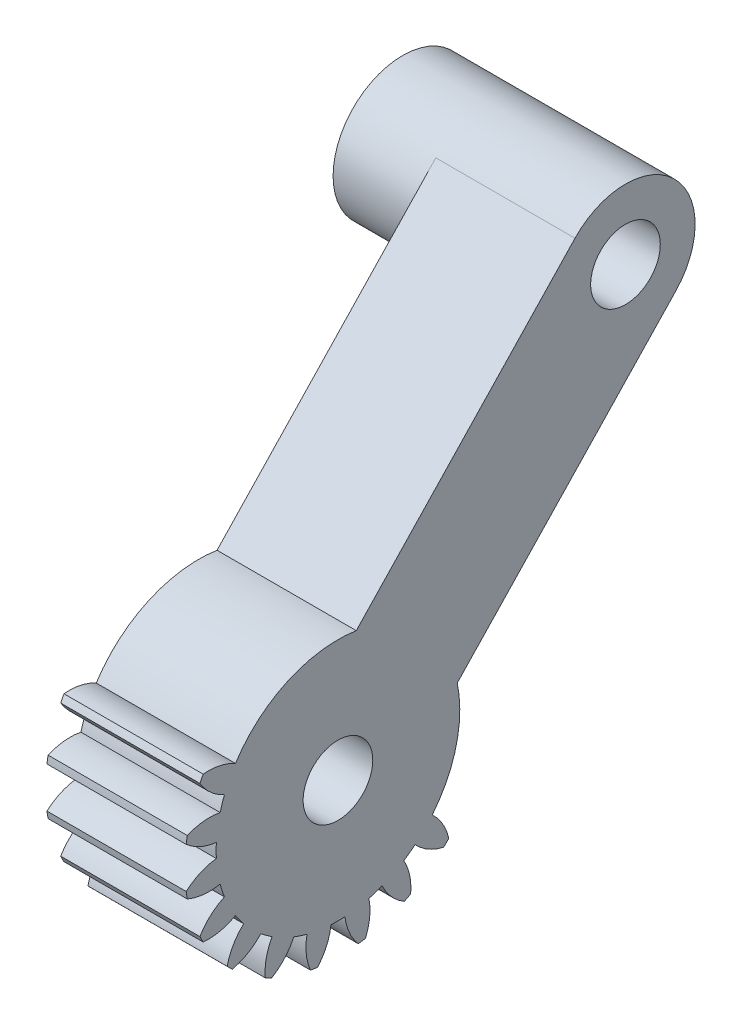
SolidWorks part; units mm, degrees
ref_plane "Front Plane" through (0, 0, 0) normal (0, 0, 1) x (1, 0, 0)
ref_plane "Top Plane" through (0, 0, 0) normal (0, 1, 0) x (1, 0, 0)
ref_plane "Right Plane" through (0, 0, 0) normal (1, 0, 0) x (0, 0, -1)
ref_plane "Plane1" through (4.0439, 0, 0) normal (1, 0, 0) x (0, 0, -1)
sketch "Sketch1" plane through (4.0439, 0, 0) normal (1, 0, 0) x (0, 0, -1)
  circle A0 centre (0.8725, -1.1221) radius 2.5
  arc A1 (-10.0295, 0.3429) -> (-7.8622, -0.6222) centre (-7.392, 3.3501) ccw
  arc A2 (-7.8622, -0.6222) -> (-7.8622, -1.622) centre (0.8725, -1.1221) ccw
  arc A3 (-7.8622, -1.622) -> (-10.0295, -2.587) centre (-7.392, -5.5943) ccw
  arc A4 (-10.0295, -2.587) -> (-9.9487, -3.0977) centre (0.8725, -1.1221) ccw
  arc A5 (-9.9487, -3.0977) -> (-7.5892, -3.3458) centre (-8.3695, 0.5774) ccw
  arc A6 (-7.5892, -3.3458) -> (-7.2802, -4.2967) centre (0.8725, -1.1221) ccw
  arc A7 (-7.2802, -4.2967) -> (-9.0433, -5.8842) centre (-5.6055, -7.9292) ccw
  arc A8 (-9.0433, -5.8842) -> (-8.8085, -6.3449) centre (0.8725, -1.1221) ccw
  arc A9 (-8.8085, -6.3449) -> (-6.4879, -5.8518) centre (-8.4423, -2.3617) ccw
  arc A10 (-6.4879, -5.8518) -> (-5.9002, -6.6607) centre (0.8725, -1.1221) ccw
  arc A11 (-5.9002, -6.6607) -> (-7.0864, -8.7153) centre (-3.185, -9.5979) ccw
  arc A12 (-7.0864, -8.7153) -> (-6.7207, -9.0809) centre (0.8725, -1.1221) ccw
  arc A13 (-6.7207, -9.0809) -> (-4.6661, -7.8948) centre (-7.6033, -5.1795) ccw
  arc A14 (-4.6661, -7.8948) -> (-3.8572, -8.4825) centre (0.8725, -1.1221) ccw
  arc A15 (-3.8572, -8.4825) -> (-4.3504, -10.8031) centre (-0.3672, -10.4369) ccw
  arc A16 (-4.3504, -10.8031) -> (-3.8897, -11.0378) centre (0.8725, -1.1221) ccw
  arc A17 (-3.8897, -11.0378) -> (-2.3022, -9.2748) centre (-5.9347, -7.6001) ccw
  arc A18 (-2.3022, -9.2748) -> (-1.3512, -9.5838) centre (0.8725, -1.1221) ccw
  arc A19 (-1.3512, -9.5838) -> (-1.1032, -11.9432) centre (2.5719, -10.3641) ccw
  arc A20 (-1.1032, -11.9432) -> (-0.5925, -12.0241) centre (0.8725, -1.1221) ccw
  arc A21 (-0.5925, -12.0241) -> (0.3725, -9.8568) centre (-3.5997, -9.3866) ccw
  arc A22 (0.3725, -9.8568) -> (1.3724, -9.8568) centre (0.8725, -1.1221) ccw
  arc A23 (1.3724, -9.8568) -> (2.3374, -12.0241) centre (5.3447, -9.3866) ccw
  arc A24 (2.3374, -12.0241) -> (2.8481, -11.9432) centre (0.8725, -1.1221) ccw
  arc A25 (2.8481, -11.9432) -> (3.0962, -9.5838) centre (-0.827, -10.3641) ccw
  arc A26 (3.0962, -9.5838) -> (4.0471, -9.2748) centre (0.8725, -1.1221) ccw
  arc A27 (4.0471, -9.2748) -> (5.6346, -11.0378) centre (7.6796, -7.6001) ccw
  arc A28 (5.6346, -11.0378) -> (6.0953, -10.8031) centre (0.8725, -1.1221) ccw
  arc A29 (6.0953, -10.8031) -> (5.6022, -8.4825) centre (2.1121, -10.4369) ccw
  arc A30 (5.6022, -8.4825) -> (6.411, -7.8948) centre (0.8725, -1.1221) ccw
  arc A31 (6.411, -7.8948) -> (8.4657, -9.0809) centre (9.3483, -5.1795) ccw
  arc A32 (8.4657, -9.0809) -> (8.8313, -8.7153) centre (0.8725, -1.1221) ccw
  arc A33 (8.8313, -8.7153) -> (7.6451, -6.6607) centre (4.9299, -9.5979) ccw
  arc A34 (7.6451, -6.6607) -> (8.2328, -5.8518) centre (0.8725, -1.1221) ccw
  arc A35 (8.2328, -5.8518) -> (10.5535, -6.3449) centre (10.1873, -2.3617) ccw
  arc A36 (10.5535, -6.3449) -> (10.7882, -5.8842) centre (0.8725, -1.1221) ccw
  arc A37 (10.7882, -5.8842) -> (9.0252, -4.2967) centre (7.3505, -7.9292) ccw
  arc A38 (9.0252, -4.2967) -> (9.3342, -3.3458) centre (0.8725, -1.1221) ccw
  arc A39 (9.3342, -3.3458) -> (11.6936, -3.0977) centre (10.1144, 0.5774) ccw
  arc A40 (11.6936, -3.0977) -> (11.7745, -2.587) centre (0.8725, -1.1221) ccw
  arc A41 (11.7745, -2.587) -> (9.6072, -1.622) centre (9.137, -5.5943) ccw
  arc A42 (9.6072, -1.622) -> (9.6072, -0.6222) centre (0.8725, -1.1221) ccw
  arc A43 (9.6072, -0.6222) -> (11.7745, 0.3429) centre (9.137, 3.3501) ccw
  arc A44 (11.7745, 0.3429) -> (11.6936, 0.8536) centre (0.8725, -1.1221) ccw
  arc A45 (11.6936, 0.8536) -> (9.3342, 1.1016) centre (10.1144, -2.8215) ccw
  arc A46 (9.3342, 1.1016) -> (9.0252, 2.0526) centre (0.8725, -1.1221) ccw
  arc A47 (9.0252, 2.0526) -> (10.7882, 3.6401) centre (7.3505, 5.6851) ccw
  arc A48 (10.7882, 3.6401) -> (10.5535, 4.1008) centre (0.8725, -1.1221) ccw
  arc A49 (10.5535, 4.1008) -> (8.2328, 3.6076) centre (10.1873, 0.1176) ccw
  arc A50 (8.2328, 3.6076) -> (7.6451, 4.4165) centre (0.8725, -1.1221) ccw
  arc A51 (7.6451, 4.4165) -> (8.8313, 6.4711) centre (4.9299, 7.3537) ccw
  arc A52 (8.8313, 6.4711) -> (8.4657, 6.8368) centre (0.8725, -1.1221) ccw
  arc A53 (8.4657, 6.8368) -> (6.411, 5.6506) centre (9.3483, 2.9353) ccw
  arc A54 (6.411, 5.6506) -> (5.6022, 6.2383) centre (0.8725, -1.1221) ccw
  arc A55 (5.6022, 6.2383) -> (6.0953, 8.5589) centre (2.1121, 8.1927) ccw
  arc A56 (6.0953, 8.5589) -> (5.6346, 8.7937) centre (0.8725, -1.1221) ccw
  arc A57 (5.6346, 8.7937) -> (4.0471, 7.0306) centre (7.6796, 5.3559) ccw
  arc A58 (4.0471, 7.0306) -> (3.0962, 7.3396) centre (0.8725, -1.1221) ccw
  arc A59 (3.0962, 7.3396) -> (2.8481, 9.6991) centre (-0.827, 8.1199) ccw
  arc A60 (2.8481, 9.6991) -> (2.3374, 9.7799) centre (0.8725, -1.1221) ccw
  arc A61 (2.3374, 9.7799) -> (1.3724, 7.6126) centre (5.3447, 7.1424) ccw
  arc A62 (1.3724, 7.6126) -> (0.3725, 7.6126) centre (0.8725, -1.1221) ccw
  arc A63 (0.3725, 7.6126) -> (-0.5925, 9.7799) centre (-3.5997, 7.1424) ccw
  arc A64 (-0.5925, 9.7799) -> (-1.1032, 9.6991) centre (0.8725, -1.1221) ccw
  arc A65 (-1.1032, 9.6991) -> (-1.3512, 7.3396) centre (2.5719, 8.1199) ccw
  arc A66 (-1.3512, 7.3396) -> (-2.3022, 7.0306) centre (0.8725, -1.1221) ccw
  arc A67 (-2.3022, 7.0306) -> (-3.8897, 8.7937) centre (-5.9347, 5.3559) ccw
  arc A68 (-3.8897, 8.7937) -> (-4.3504, 8.5589) centre (0.8725, -1.1221) ccw
  arc A69 (-4.3504, 8.5589) -> (-3.8572, 6.2383) centre (-0.3672, 8.1927) ccw
  arc A70 (-3.8572, 6.2383) -> (-4.6661, 5.6506) centre (0.8725, -1.1221) ccw
  arc A71 (-4.6661, 5.6506) -> (-6.7207, 6.8368) centre (-7.6033, 2.9353) ccw
  arc A72 (-6.7207, 6.8368) -> (-7.0864, 6.4711) centre (0.8725, -1.1221) ccw
  arc A73 (-7.0864, 6.4711) -> (-5.9002, 4.4165) centre (-3.185, 7.3537) ccw
  arc A74 (-5.9002, 4.4165) -> (-6.4879, 3.6076) centre (0.8725, -1.1221) ccw
  arc A75 (-6.4879, 3.6076) -> (-8.8085, 4.1008) centre (-8.4423, 0.1176) ccw
  arc A76 (-8.8085, 4.1008) -> (-9.0433, 3.6401) centre (0.8725, -1.1221) ccw
  arc A77 (-9.0433, 3.6401) -> (-7.2802, 2.0526) centre (-5.6055, 5.6851) ccw
  arc A78 (-7.2802, 2.0526) -> (-7.5892, 1.1016) centre (0.8725, -1.1221) ccw
  arc A79 (-7.5892, 1.1016) -> (-9.9487, 0.8536) centre (-8.3695, -2.8215) ccw
  arc A80 (-9.9487, 0.8536) -> (-10.0295, 0.3429) centre (0.8725, -1.1221) ccw
extrude "Boss-Extrude1" add sketch "Sketch1" against normal blind 10
sketch "Sketch2" plane through (4.0439, 0, 0) normal (1, 0, 0) x (0, 0, -1)
  line L0 (0.8725, -1.1221) -> (21.5231, 20.6392) construction
  line L1 (-2.7544, 2.3197) -> (17.8962, 24.0809)
  line L2 (4.4993, -4.5639) -> (25.15, 17.1974)
  line L3 (0.8725, 18.0125) -> (0.8725, -1.1221) construction
  arc A0 (-2.7544, 2.3197) -> (4.4993, -4.5639) centre (0.8725, -1.1221) ccw
  arc A1 (25.15, 17.1974) -> (17.8962, 24.0809) centre (21.5231, 20.6392) ccw
  arc A2 (25.1179, 24.1144) -> (24.8055, 24.4109) centre (21.5231, 20.6392) ccw
  circle A3 centre (21.5231, 20.6392) radius 2.5
  point P3 (11.1978, 9.7585)
  dimension "D2" = 5
  dimension "D1" = 10
  dimension "D3" = 30
  dimension "D4" = 43.5
extrude "Boss-Extrude2" add sketch "Sketch2" against normal blind 10
sketch "Sketch3" plane through (-5.9561, 0, 0) normal (-1, 0, 0) x (0, 0, 1)
  circle A0 centre (-21.5231, 20.6392) radius 2.5
  circle A1 centre (-21.5231, 20.6392) radius 5
extrude "Boss-Extrude3" add sketch "Sketch3" along normal blind 6
sketch "Sketch4" plane through (4.0439, 0, 0) normal (1, 0, 0) x (0, 0, -1)
  circle A1 centre (0.8725, -1.1221) radius 2.5
  dimension "D1" = 5
extrude "Cut-Extrude1" cut sketch "Sketch4" against normal through all
sketch "Sketch5" plane through (4.0439, 0, 0) normal (1, 0, 0) x (0, 0, -1)
  circle A0 centre (0.8725, -1.1221) radius 9.5546
sketch "Sketch6" plane through (4.0439, 0, 0) normal (1, 0, 0) x (0, 0, -1)
  line L0 (4.5797, 10.0482) -> (2.1876, 7.5275)
  line L2 (11.8334, 3.1647) -> (9.4414, 0.644)
  line L4 (7.9481, -6.2679) -> (10.3909, -8.0444)
  line L5 (-6.161, 4.0813) -> (-8.5892, 5.8777)
  arc A0 (2.1876, 7.5275) -> (-6.161, 4.0813) centre (0.8725, -1.1221) ccw
  arc A1 (4.5797, 10.0482) -> (-8.5892, 5.8777) centre (0.8725, -1.1221) ccw
  arc A2 (7.9481, -6.2679) -> (9.4414, 0.644) centre (0.8725, -1.1221) ccw
  arc A3 (10.3909, -8.0444) -> (11.8334, 3.1647) centre (0.8725, -1.1221) ccw
extrude "Cut-Extrude2" cut sketch "Sketch6" against normal through all
